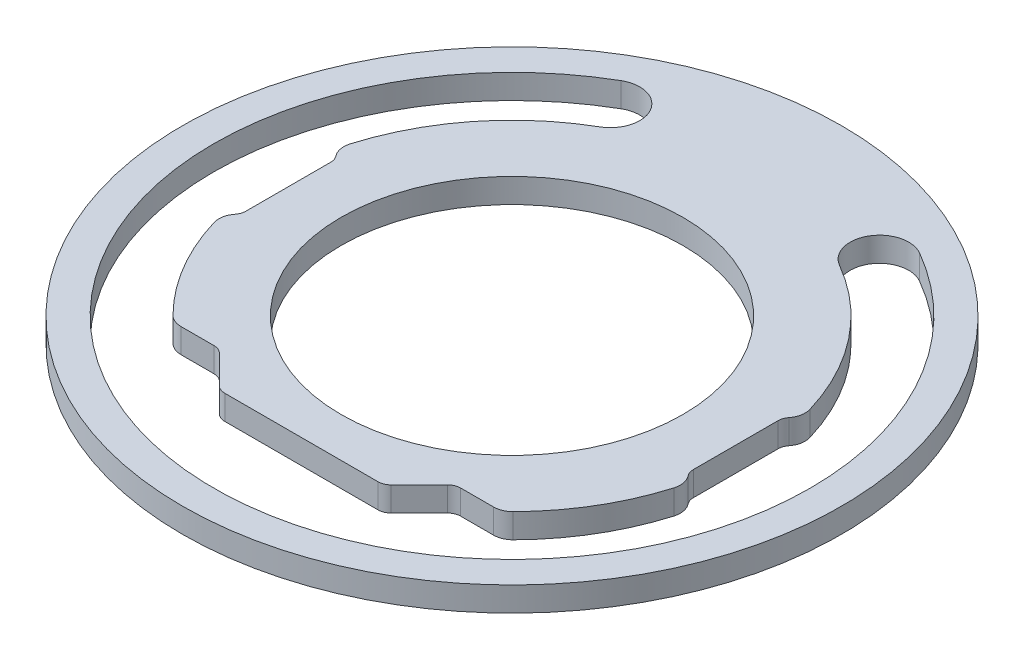
SolidWorks part; units mm, degrees
ref_plane "Front Plane" through (0, 0, 0) normal (0, 0, 1) x (1, 0, 0)
ref_plane "Top Plane" through (0, 0, 0) normal (0, 1, 0) x (1, 0, 0)
ref_plane "Right Plane" through (0, 0, 0) normal (1, 0, 0) x (0, 0, -1)
sketch "Sketch1" plane through (0, 0, 0) normal (0, 1, 0) x (1, 0, 0)
  circle A0 centre (0, 0) radius 22.225
  circle A1 centre (0, 0) radius 42.8625
  point P16 (0.3175, -0.3175)
  point P17 (0, 0)
  dimension "D1" = 44.45
  dimension "D2" = 85.725
extrude "Boss-Extrude1" add sketch "Sketch1" along normal blind 3.175
sketch "Sketch2" plane through (0, 3.175, 0) normal (0, 1, 0) x (1, 0, 0)
  line L0 (0, 0) -> (17.4943, 30.3009) construction
  line L2 (0, 0) -> (0, 42.8625) construction
  line L3 (0, 0) -> (-17.4943, 30.3009) construction
  arc A0 (19.3993, 33.6005) -> (15.5893, 27.0014) centre (17.4943, 30.3009) ccw
  circle A1 centre (0, 0) radius 42.8625 construction
  arc A2 (-15.5893, 27.0014) -> (-19.3993, 33.6005) centre (-17.4943, 30.3009) ccw
  arc A3 (-19.3993, 33.6005) -> (19.3993, 33.6005) centre (0, 0) ccw
  arc A4 (-15.5893, 27.0014) -> (15.5893, 27.0014) centre (0, 0) ccw
  dimension "D1" = 7.62
  dimension "D7" = 7.62
  dimension "D6" = 34.9885
extrude "Cut-Extrude1" cut sketch "Sketch2" against normal through all
sketch "Sketch3" plane through (0, 3.175, 0) normal (0, 1, 0) x (1, 0, 0)
  line L0 (0, 42.8625) -> (0, -42.8625) construction
  circle A0 centre (0, 0) radius 42.8625 construction
sketch "Sketch6" plane through (0, 3.175, 0) normal (0, 1, 0) x (1, 0, 0)
  line L1 (-21.3499, -22.7218) -> (-16.0371, -22.7218)
  line L2 (-14.8421, -23.2168) -> (-11.165, -26.8939)
  line L3 (-9.97, -27.3889) -> (9.97, -27.3889)
  line L4 (11.165, -26.8939) -> (14.8421, -23.2168)
  line L5 (16.0371, -22.7218) -> (21.3499, -22.7218)
  line L8 (29.1, -5.51) -> (29.1, 5.51)
  line L11 (21.3499, 22.7218) -> (16.0371, 22.7218)
  line L12 (14.8421, 23.2168) -> (11.165, 26.8939)
  line L14 (-11.165, 26.8939) -> (-14.8421, 23.2168)
  line L15 (-16.0371, 22.7218) -> (-21.3499, 22.7218)
  line L18 (-29.1, 5.51) -> (-29.1, -5.51)
  line L20 (-29.1, 0) -> (29.1, 0) construction
  line L21 (0, -27.3889) -> (0, 27.3889) construction
  line L22 (0, 0) -> (-68.6787, 0) construction
  line L24 (9.97, 27.3889) -> (15.0374, 27.3889)
  line L25 (-14.1947, 32.2059) -> (-9.97, 27.3889)
  arc A0 (-14.8421, -23.2168) -> (-16.0371, -22.7218) centre (-16.0371, -24.4118) ccw
  arc A1 (-11.165, -26.8939) -> (-9.97, -27.3889) centre (-9.97, -25.6989) ccw
  arc A2 (9.97, -27.3889) -> (11.165, -26.8939) centre (9.97, -25.6989) ccw
  arc A3 (16.0371, -22.7218) -> (14.8421, -23.2168) centre (16.0371, -24.4118) ccw
  arc A4 (29.1, -5.51) -> (30.3496, -7.1416) centre (30.79, -5.51) ccw
  arc A5 (30.3496, 7.1416) -> (29.1, 5.51) centre (30.79, 5.51) ccw
  arc A6 (14.8421, 23.2168) -> (16.0371, 22.7218) centre (16.0371, 24.4118) ccw
  arc A7 (11.165, 26.8939) -> (9.97, 27.3889) centre (9.97, 25.6989) ccw
  arc A8 (-9.97, 27.3889) -> (-11.165, 26.8939) centre (-9.97, 25.6989) ccw
  arc A9 (-16.0371, 22.7218) -> (-14.8421, 23.2168) centre (-16.0371, 24.4118) ccw
  arc A10 (-29.1, 5.51) -> (-30.3496, 7.1416) centre (-30.79, 5.51) ccw
  arc A11 (-30.3496, -7.1416) -> (-29.1, -5.51) centre (-30.79, -5.51) ccw
  arc A16 (30.3496, -7.1416) -> (30.3496, 7.1416) centre (0, 0) ccw
  arc A17 (-15.5893, 27.0014) -> (-21.3499, 22.7218) centre (0, 0) ccw
  arc A18 (-30.3496, 7.1416) -> (-30.3496, -7.1416) centre (0, 0) ccw
  arc A19 (-21.3499, -22.7218) -> (21.3499, -22.7218) centre (0, 0) ccw
  arc A20 (19.3993, 33.6005) -> (15.5893, 27.0014) centre (17.4943, 30.3009) ccw construction
  arc A21 (-15.5893, 27.0014) -> (-19.3993, 33.6005) centre (-17.4943, 30.3009) ccw construction
  arc A22 (-14.1947, 32.2059) -> (-15.5893, 27.0014) centre (-17.4943, 30.3009) cw
  point P48 (0, 0)
  dimension "D1" = 0
extrude "Cut-Extrude3" cut sketch "Sketch6" against normal through all
fillet "Fillet1" radius 2.54 6 edges at (30.3496, 1.5875, -7.1416) (30.3496, 1.5875, 7.1416) (-30.3496, 1.5875, 7.1416) (-30.3496, 1.5875, -7.1416) (21.3499, 1.5875, 22.7218) (-21.3499, 1.5875, 22.7218)
